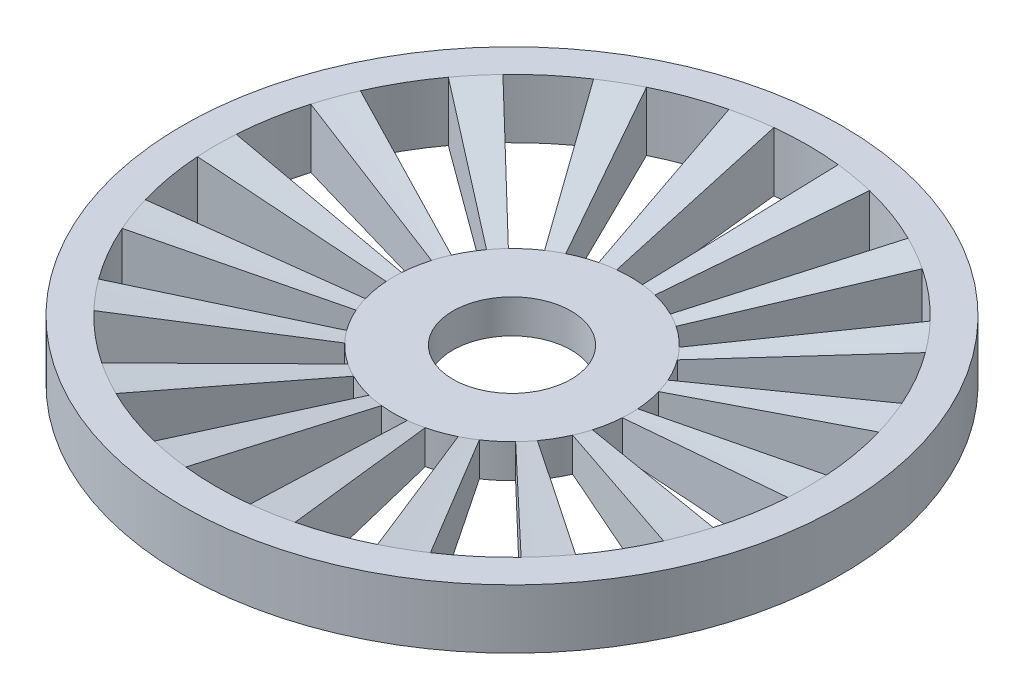
SolidWorks part; units mm, degrees
ref_plane "Front Plane" through (0, 0, 0) normal (0, 0, 1) x (1, 0, 0)
ref_plane "Top Plane" through (0, 0, 0) normal (0, 1, 0) x (1, 0, 0)
ref_plane "Right Plane" through (0, 0, 0) normal (1, 0, 0) x (0, 0, -1)
ref_plane "Plane1" through (0, 3.5, 0) normal (0, 1, 0) x (1, 0, 0)
sketch "Sketch1" plane through (0, 0, 0) normal (0, 1, 0) x (1, 0, 0)
  circle A0 centre (0, 0) radius 17.5
  circle A1 centre (0, 0) radius 19.5
  point P17 (16.7911, 4.9303)
  point P26 (14.7219, 9.4612)
  point P27 (11.4601, 13.2256)
  point P28 (7.2698, 15.9186)
  point P29 (2.4905, 17.3219)
  point P30 (-2.4905, 17.3219)
  point P31 (-7.2698, 15.9186)
  point P32 (-11.4601, 13.2256)
  point P33 (-14.7219, 9.4612)
  point P34 (-16.7911, 4.9303)
  point P35 (-17.5, 0)
  point P36 (-16.7911, -4.9303)
  point P37 (-14.7219, -9.4612)
  point P38 (-11.4601, -13.2256)
  point P39 (-7.2698, -15.9186)
  point P40 (-2.4905, -17.3219)
  point P41 (2.4905, -17.3219)
  point P42 (7.2698, -15.9186)
  point P43 (11.4601, -13.2256)
  point P44 (14.7219, -9.4612)
  point P45 (16.7911, -4.9303)
  point P46 (17.5, 0)
  dimension "D1" = 35
  dimension "D2" = 2
sketch "Sketch2" plane through (0, 0, 0) normal (0, 1, 0) x (1, 0, 0)
  circle A0 centre (0, 0) radius 7
  dimension "D1" = 14
sketch "Sketch4" plane through (0, 0, 0) normal (0, 1, 0) x (1, 0, 0)
  line L0 (0, 7) -> (0, 17.5) construction
  line L3 (1.2155, 6.8937) -> (3.0388, 17.2341) construction
  line L4 (2.3941, 6.5778) -> (5.9854, 16.4446) construction
  line L5 (3.5, 6.0622) -> (8.75, 15.1554) construction
  line L6 (4.4995, 5.3623) -> (11.2488, 13.4058) construction
  line L7 (5.3623, 4.4995) -> (13.4058, 11.2488) construction
  line L8 (6.0622, 3.5) -> (15.1554, 8.75) construction
  line L9 (6.5778, 2.3941) -> (16.4446, 5.9854) construction
  line L10 (6.8937, 1.2155) -> (17.2341, 3.0388) construction
  line L11 (7, 0) -> (17.5, 0) construction
  line L12 (6.8937, -1.2155) -> (17.2341, -3.0388) construction
  line L13 (6.5778, -2.3941) -> (16.4446, -5.9854) construction
  line L14 (6.0622, -3.5) -> (15.1554, -8.75) construction
  line L15 (5.3623, -4.4995) -> (13.4058, -11.2488) construction
  line L16 (4.4995, -5.3623) -> (11.2488, -13.4058) construction
  line L17 (3.5, -6.0622) -> (8.75, -15.1554) construction
  line L18 (2.3941, -6.5778) -> (5.9854, -16.4446) construction
  line L19 (1.2155, -6.8937) -> (3.0388, -17.2341) construction
  line L20 (0, -7) -> (0, -17.5) construction
  line L21 (-1.2155, -6.8937) -> (-3.0388, -17.2341) construction
  line L22 (-2.3941, -6.5778) -> (-5.9854, -16.4446) construction
  line L23 (-3.5, -6.0622) -> (-8.75, -15.1554) construction
  line L24 (-4.4995, -5.3623) -> (-11.2488, -13.4058) construction
  line L25 (-5.3623, -4.4995) -> (-13.4058, -11.2488) construction
  line L26 (-6.0622, -3.5) -> (-15.1554, -8.75) construction
  line L27 (-6.5778, -2.3941) -> (-16.4446, -5.9854) construction
  line L28 (-6.8937, -1.2155) -> (-17.2341, -3.0388) construction
  line L29 (-7, 0) -> (-17.5, 0) construction
  line L30 (-6.8937, 1.2155) -> (-17.2341, 3.0388) construction
  line L31 (-6.5778, 2.3941) -> (-16.4446, 5.9854) construction
  line L32 (-6.0622, 3.5) -> (-15.1554, 8.75) construction
  line L33 (-5.3623, 4.4995) -> (-13.4058, 11.2488) construction
  line L34 (-4.4995, 5.3623) -> (-11.2488, 13.4058) construction
  line L35 (-3.5, 6.0622) -> (-8.75, 15.1554) construction
  line L36 (-2.3941, 6.5778) -> (-5.9854, 16.4446) construction
  line L37 (-1.2155, 6.8937) -> (-3.0388, 17.2341) construction
  line L39 (0.7614, 6.9585) -> (1.9036, 17.3962)
  line L42 (1.6644, 6.7992) -> (4.161, 16.9981)
  line L43 (3.0955, 6.2784) -> (7.7386, 15.696)
  line L44 (3.8895, 5.8199) -> (9.7238, 14.5498)
  line L45 (5.0561, 4.8411) -> (12.6403, 12.1026)
  line L46 (5.6455, 4.1387) -> (14.1137, 10.3466)
  line L47 (6.4069, 2.8198) -> (16.0173, 7.0495)
  line L48 (6.7205, 1.9582) -> (16.8013, 4.8955)
  line L49 (6.985, 0.4585) -> (17.4624, 1.1461)
  line L50 (6.985, -0.4585) -> (17.4624, -1.1461)
  line L51 (6.7205, -1.9582) -> (16.8013, -4.8955)
  line L52 (6.4069, -2.8198) -> (16.0173, -7.0495)
  line L53 (5.6455, -4.1387) -> (14.1137, -10.3466)
  line L54 (5.0561, -4.8411) -> (12.6403, -12.1026)
  line L55 (3.8895, -5.8199) -> (9.7238, -14.5498)
  line L56 (3.0955, -6.2784) -> (7.7386, -15.696)
  line L57 (1.6644, -6.7992) -> (4.161, -16.9981)
  line L58 (0.7614, -6.9585) -> (1.9036, -17.3962)
  line L59 (-0.7614, -6.9585) -> (-1.9036, -17.3962)
  line L60 (-1.6644, -6.7992) -> (-4.161, -16.9981)
  line L61 (-3.0955, -6.2784) -> (-7.7386, -15.696)
  line L62 (-3.8895, -5.8199) -> (-9.7238, -14.5498)
  line L63 (-5.0561, -4.8411) -> (-12.6403, -12.1026)
  line L64 (-5.6455, -4.1387) -> (-14.1137, -10.3466)
  line L65 (-6.4069, -2.8198) -> (-16.0173, -7.0495)
  line L66 (-6.7205, -1.9582) -> (-16.8013, -4.8955)
  line L67 (-6.985, -0.4585) -> (-17.4624, -1.1461)
  line L68 (-6.985, 0.4585) -> (-17.4624, 1.1461)
  line L69 (-6.7205, 1.9582) -> (-16.8013, 4.8955)
  line L70 (-6.4069, 2.8198) -> (-16.0173, 7.0495)
  line L71 (-5.6455, 4.1387) -> (-14.1137, 10.3466)
  line L72 (-5.0561, 4.8411) -> (-12.6403, 12.1026)
  line L73 (-3.8895, 5.8199) -> (-9.7238, 14.5498)
  line L74 (-3.0955, 6.2784) -> (-7.7386, 15.696)
  line L75 (-1.6644, 6.7992) -> (-4.161, 16.9981)
  line L76 (-0.7614, 6.9585) -> (-1.9036, 17.3962)
  circle A86 centre (0, 0) radius 7 construction
  circle A90 centre (0, 0) radius 17.5 construction
  arc A91 (0.7614, 6.9585) -> (1.6644, 6.7992) centre (0, 0) cw
  arc A92 (4.161, 16.9981) -> (1.9036, 17.3962) centre (0, 0) ccw
  arc A93 (9.7238, 14.5498) -> (7.7386, 15.696) centre (0, 0) ccw
  arc A94 (3.0955, 6.2784) -> (3.8895, 5.8199) centre (0, 0) cw
  arc A95 (14.1137, 10.3466) -> (12.6403, 12.1026) centre (0, 0) ccw
  arc A96 (5.0561, 4.8411) -> (5.6455, 4.1387) centre (0, 0) cw
  arc A97 (16.8013, 4.8955) -> (16.0173, 7.0495) centre (0, 0) ccw
  arc A98 (6.4069, 2.8198) -> (6.7205, 1.9582) centre (0, 0) cw
  arc A99 (17.4624, -1.1461) -> (17.4624, 1.1461) centre (0, 0) ccw
  arc A100 (6.985, 0.4585) -> (6.985, -0.4585) centre (0, 0) cw
  arc A101 (16.0173, -7.0495) -> (16.8013, -4.8955) centre (0, 0) ccw
  arc A102 (6.7205, -1.9582) -> (6.4069, -2.8198) centre (0, 0) cw
  arc A103 (12.6403, -12.1026) -> (14.1137, -10.3466) centre (0, 0) ccw
  arc A104 (5.6455, -4.1387) -> (5.0561, -4.8411) centre (0, 0) cw
  arc A105 (7.7386, -15.696) -> (9.7238, -14.5498) centre (0, 0) ccw
  arc A106 (3.8895, -5.8199) -> (3.0955, -6.2784) centre (0, 0) cw
  arc A107 (1.9036, -17.3962) -> (4.161, -16.9981) centre (0, 0) ccw
  arc A108 (1.6644, -6.7992) -> (0.7614, -6.9585) centre (0, 0) cw
  arc A109 (-4.161, -16.9981) -> (-1.9036, -17.3962) centre (0, 0) ccw
  arc A110 (-0.7614, -6.9585) -> (-1.6644, -6.7992) centre (0, 0) cw
  arc A111 (-9.7238, -14.5498) -> (-7.7386, -15.696) centre (0, 0) ccw
  arc A112 (-3.0955, -6.2784) -> (-3.8895, -5.8199) centre (0, 0) cw
  arc A113 (-14.1137, -10.3466) -> (-12.6403, -12.1026) centre (0, 0) ccw
  arc A114 (-5.0561, -4.8411) -> (-5.6455, -4.1387) centre (0, 0) cw
  arc A115 (-16.8013, -4.8955) -> (-16.0173, -7.0495) centre (0, 0) ccw
  arc A116 (-6.4069, -2.8198) -> (-6.7205, -1.9582) centre (0, 0) cw
  arc A117 (-17.4624, 1.1461) -> (-17.4624, -1.1461) centre (0, 0) ccw
  arc A118 (-6.985, -0.4585) -> (-6.985, 0.4585) centre (0, 0) cw
  arc A119 (-16.0173, 7.0495) -> (-16.8013, 4.8955) centre (0, 0) ccw
  arc A120 (-6.7205, 1.9582) -> (-6.4069, 2.8198) centre (0, 0) cw
  arc A121 (-12.6403, 12.1026) -> (-14.1137, 10.3466) centre (0, 0) ccw
  arc A122 (-5.6455, 4.1387) -> (-5.0561, 4.8411) centre (0, 0) cw
  arc A123 (-7.7386, 15.696) -> (-9.7238, 14.5498) centre (0, 0) ccw
  arc A124 (-3.8895, 5.8199) -> (-3.0955, 6.2784) centre (0, 0) cw
  arc A125 (-1.9036, 17.3962) -> (-4.161, 16.9981) centre (0, 0) ccw
  arc A126 (-1.6644, 6.7992) -> (-0.7614, 6.9585) centre (0, 0) cw
  point P49 (0, 0)
  point P80 (0, 0)
  point P153 (0, 0)
  point P188 (0, 0)
  dimension "D2" = 35
  dimension "D3" = 14
  dimension "D1" = 36
  dimension "D4" = 18
extrude "Boss-Extrude1" add sketch "Sketch1" along normal up to surface (3.5 mm away) up to plane "Plane1"
extrude "Boss-Extrude2" add sketch "Sketch2" along normal blind 2 separate body
extrude "Boss-Extrude3" add sketch "Sketch4" along normal up to surface (3.5 mm away) up to plane "Plane1"
sketch "Sketch6" plane through (0, 0, 0) normal (0, 0, 1) x (1, 0, 0)
  line L0 (0, -983.4456) -> (0, 49016.5544) construction
sketch "Sketch7" plane through (0, 0, 0) normal (0, 0, 1) x (1, 0, 0)
  line L0 (7, 2) -> (17.5, 3.5)
  line L2 (17.5, 3.5) -> (7, 3.5)
  line L3 (7, 3.5) -> (7, 2)
  line L4 (1.6644, 2) -> (0.7614, 2) construction
  line L6 (16.7911, 3.5) -> (14.7219, 3.5) construction
revolve "Cut-Revolve1" cut sketch "Sketch7" angle 360 about L0
sketch "Sketch8" plane through (0, 2, 0) normal (0, 1, 0) x (1, 0, 0)
  circle A0 centre (0, 0) radius 3.5
  dimension "D1" = 7
extrude "Cut-Extrude1" cut sketch "Sketch8" against normal through all
sketch "Sketch9" plane through (0, 0, 0) normal (0, -1, 0) x (1, 0, 0)
  line L1 (-4.35, 4.35) -> (4.35, 4.35)
  line L2 (-4.35, 4.35) -> (-4.35, -4.35)
  line L3 (-4.35, -4.35) -> (4.35, -4.35)
  line L4 (4.35, 4.35) -> (4.35, -4.35)
  line L5 (-4.35, 4.35) -> (4.35, -4.35) construction
  line L6 (-4.35, -4.35) -> (4.35, 4.35) construction
  circle A2 centre (0, 0) radius 7
  dimension "D1" = 8.7
